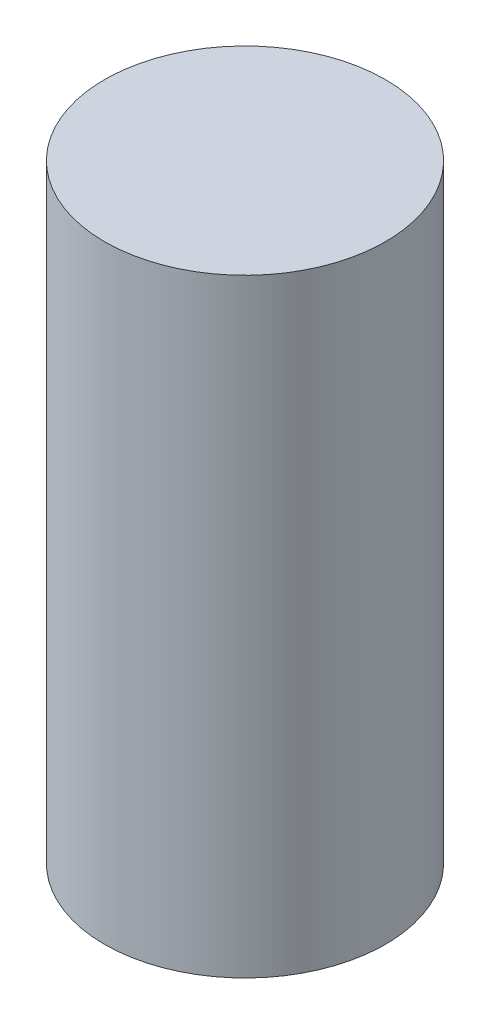
SolidWorks part; units mm, degrees
ref_plane "Front Plane" through (0, 0, 0) normal (0, 0, 1) x (1, 0, 0)
ref_plane "Top Plane" through (0, 0, 0) normal (0, 1, 0) x (1, 0, 0)
ref_plane "Right Plane" through (0, 0, 0) normal (1, 0, 0) x (0, 0, -1)
sketch "Sketch1" plane through (0, 0, 0) normal (0, 1, 0) x (1, 0, 0)
  circle A0 centre (0, 0) radius 45
  dimension "D1" = 90
extrude "Boss-Extrude1" add sketch "Sketch1" along normal blind 195
